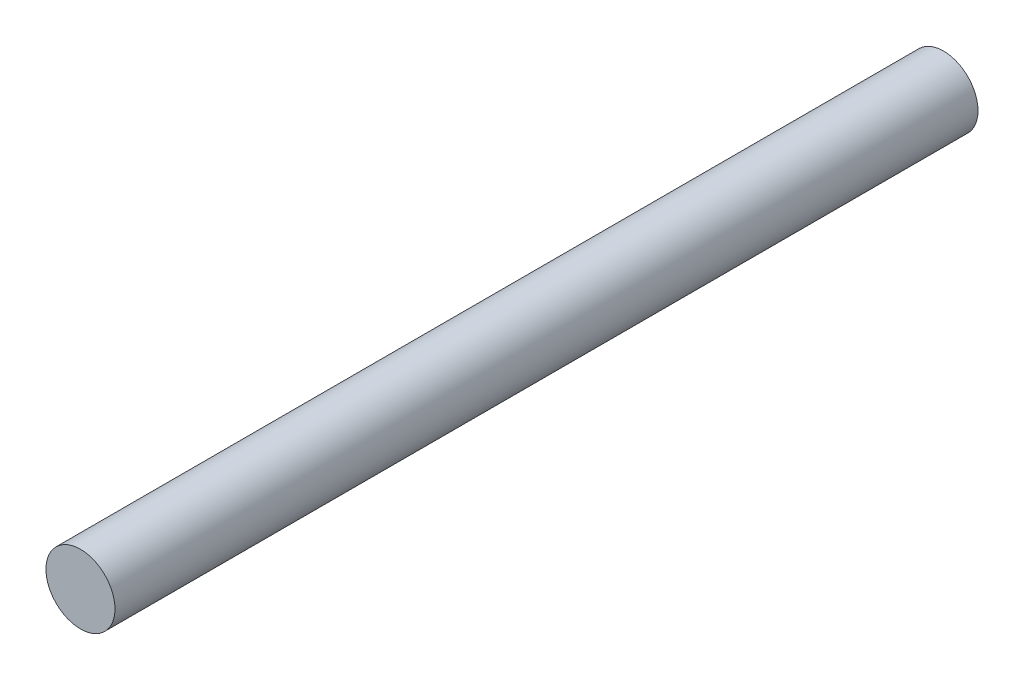
SolidWorks part; units mm, degrees
ref_plane "Front Plane" through (0, 0, 0) normal (0, 0, 1) x (1, 0, 0)
ref_plane "Top Plane" through (0, 0, 0) normal (0, 1, 0) x (1, 0, 0)
ref_plane "Right Plane" through (0, 0, 0) normal (1, 0, 0) x (0, 0, -1)
sketch "Sketch2" plane through (0, 0, 0) normal (0, 0, 1) x (1, 0, 0)
  circle A0 centre (0, 0) radius 6
  dimension "D1" = 12
extrude "Boss-Extrude1" add sketch "Sketch2" along normal blind 150
